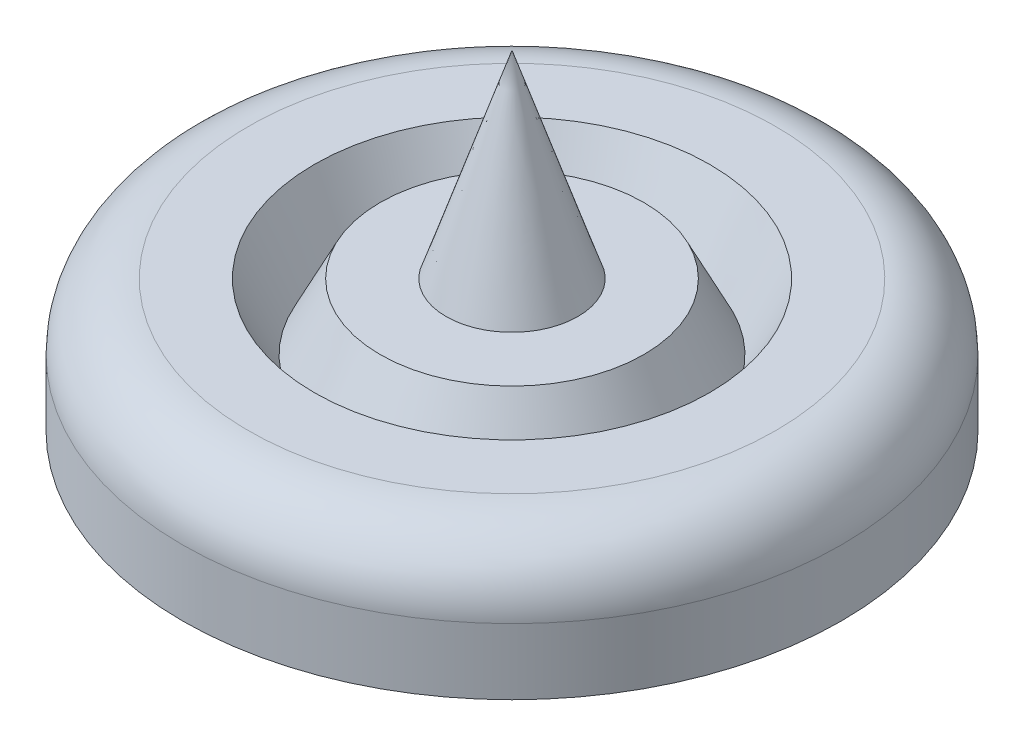
SolidWorks part; units mm, degrees
ref_plane "Front Plane" through (0, 0, 0) normal (0, 0, 1) x (1, 0, 0)
ref_plane "Top Plane" through (0, 0, 0) normal (0, 1, 0) x (1, 0, 0)
ref_plane "Right Plane" through (0, 0, 0) normal (1, 0, 0) x (0, 0, -1)
sketch "Sketch1" plane through (0, 0, 0) normal (0, 0, 1) x (1, 0, 0)
  line L0 (0, 0) -> (25.4, 0) construction
  line L1 (25.4, 0) -> (0, 25.4)
  line L2 (0, 25.4) -> (0, 0) construction
  line L3 (25.4, 0) -> (127, 0)
  line L4 (127, 0) -> (127, 50.8)
  line L5 (127, 50.8) -> (76.2, 50.8)
  line L6 (76.2, 50.8) -> (63.5, 25.4)
  line L7 (63.5, 25.4) -> (50.8, 50.8)
  line L8 (50.8, 50.8) -> (25.4, 50.8)
  line L9 (25.4, 50.8) -> (0, 127)
  line L10 (0, 127) -> (0, 25.4)
  dimension "D1" = 101.6
  dimension "D2" = 101.6
  dimension "D3" = 50.8
  dimension "D4" = 50.8
  dimension "D5" = 25.4
  dimension "D6" = 25.4
  dimension "D7" = 25.4
  dimension "D8" = 25.4
  dimension "D9" = 76.2
  dimension "D10" = 12.7
  dimension "D11" = 25.4
revolve "Revolve1" add sketch "Sketch1" angle 360 about L10
fillet "Fillet1" radius 25.4 1 edges at (-127, 50.8, 0)
